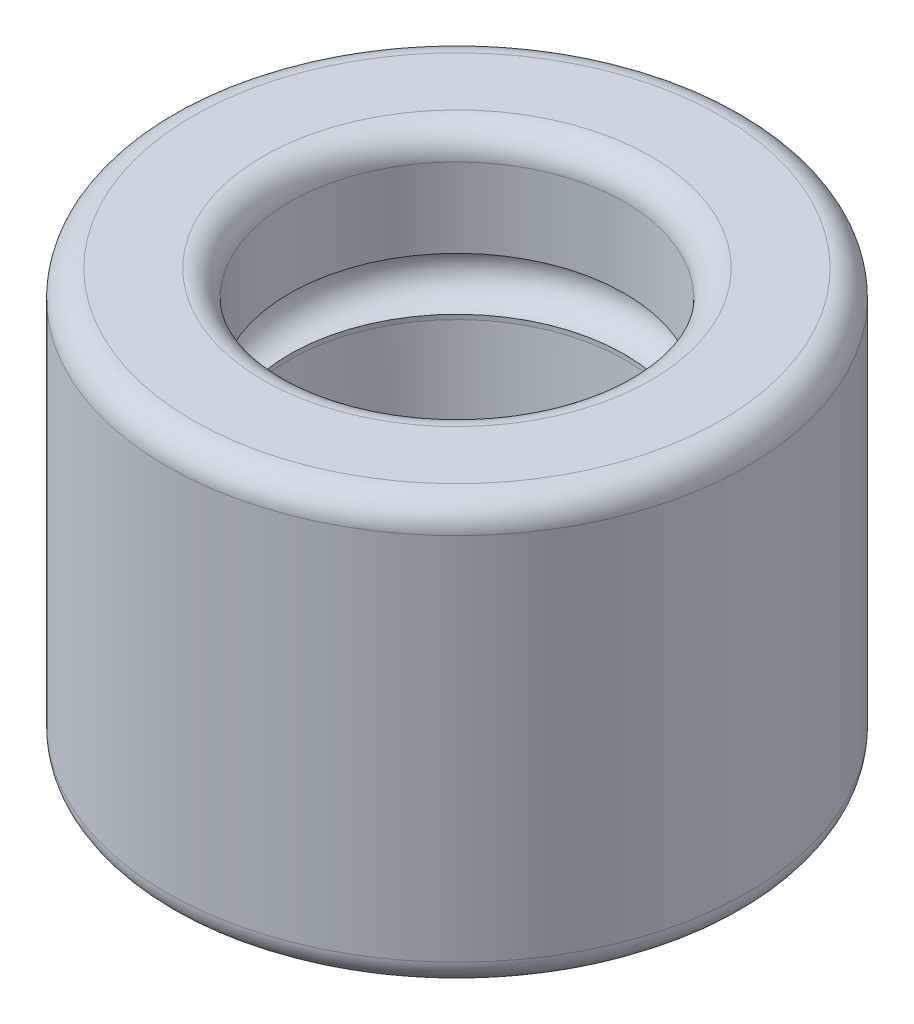
SolidWorks part; units mm, degrees
ref_plane "Front Plane" through (0, 0, 0) normal (0, 0, 1) x (1, 0, 0)
ref_plane "Top Plane" through (0, 0, 0) normal (0, 1, 0) x (1, 0, 0)
ref_plane "Right Plane" through (0, 0, 0) normal (1, 0, 0) x (0, 0, -1)
sketch "Sketch3" plane through (0, 0, 0) normal (0, 0, 1) x (1, 0, 0)
  line L0 (0, 0) -> (0, 63.603) construction
  line L1 (0, 0) -> (-5.5, 0)
  line L2 (-5.5, 0) -> (-5.5, 8)
  line L3 (-5.5, 8) -> (-3.175, 8)
  line L4 (-3.175, 8) -> (-3.175, 6)
  line L5 (-3.175, 1.4832) -> (0, 1.4832)
  line L6 (0, 1.4832) -> (0, 0)
  line L7 (-3.175, 5) -> (-3.175, 1.4832)
  arc A0 (-3.175, 6) -> (-3.175, 5) centre (-3.175, 5.5) ccw
  dimension "D6" = 1
  dimension "D1" = 3.175
  dimension "D2" = 5.5
  dimension "D3" = 8
  dimension "D4" = 1.4832
  dimension "D5" = 2.5
revolve "Revolve1" add sketch "Sketch3" angle 360 about L0
chamfer "Chamfer1" distance 0.3 angle 85 1 edges at (0, 1.4832, -3.175)
fillet "Fillet1" radius 0.5 3 edges at (0, 0, -5.5) (0, 8, -3.175) (0, 8, -5.5)
equation "\".5.00mm\"=1"
